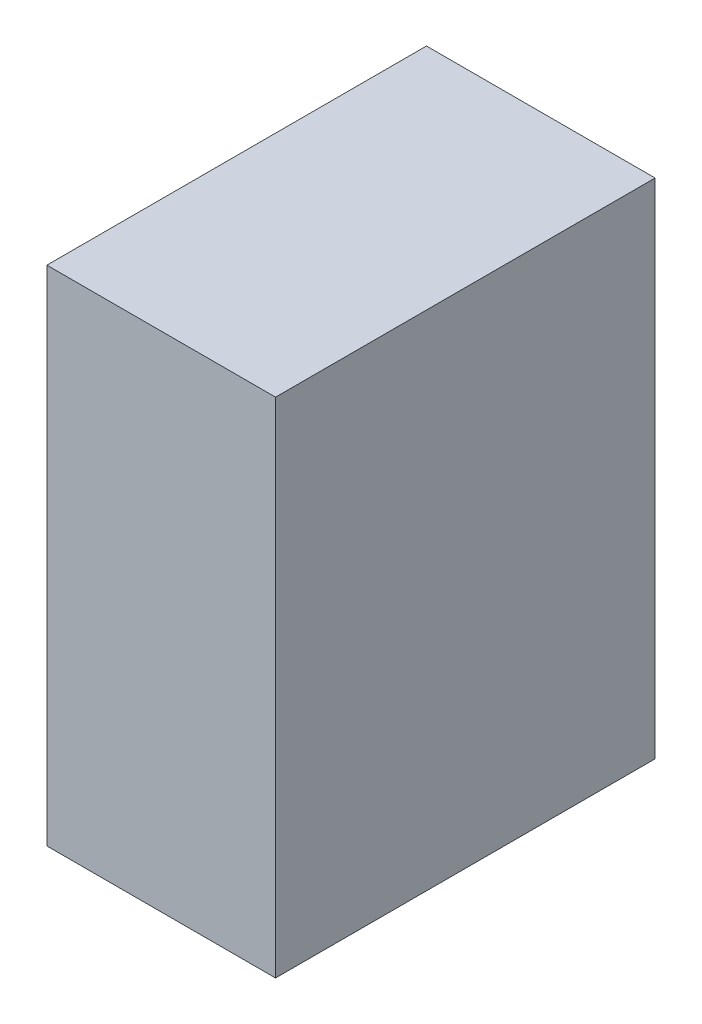
SolidWorks part; units mm, degrees
ref_plane "Front Plane" through (0, 0, 0) normal (0, 0, 1) x (1, 0, 0)
ref_plane "Top Plane" through (0, 0, 0) normal (0, 1, 0) x (1, 0, 0)
ref_plane "Right Plane" through (0, 0, 0) normal (1, 0, 0) x (0, 0, -1)
sketch "Sketch1" plane through (0, 0, 0) normal (0, 0, 1) x (1, 0, 0)
  line L1 (6.35, -12.7) -> (-6.35, -12.7)
  line L2 (6.35, -12.7) -> (6.35, 12.7)
  line L3 (6.35, 12.7) -> (-6.35, 12.7)
  line L4 (-6.35, -12.7) -> (-6.35, 12.7)
  line L5 (6.35, -12.7) -> (-6.35, 12.7) construction
  line L6 (6.35, 12.7) -> (-6.35, -12.7) construction
  point P0 (0, 0)
  dimension "D1" = 12.7
  dimension "D2" = 25.4
extrude "Boss-Extrude1" add sketch "Sketch1" along normal blind 21.082
sketch "Sketch3" plane through (0, 12.7, 0) normal (0, 1, 0) x (1, 0, 0)
  line L0 (0, -21.082) -> (0, 0) construction
  line L1 (6.35, -21.082) -> (-6.35, -21.082) construction
  line L2 (-6.35, -21.082) -> (-6.35, 0) construction
  line L3 (4.064, -18.542) -> (-4.064, -18.542)
  line L4 (4.064, -18.542) -> (4.064, -5.334)
  line L5 (4.064, -5.334) -> (-4.064, -5.334)
  line L6 (-4.064, -18.542) -> (-4.064, -5.334)
  dimension "D1" = 8.128
  dimension "D2" = 13.208
  dimension "D3" = 2.54
  dimension "D4" = 2.286
extrude "Cut-Extrude2" cut sketch "Sketch3" against normal blind 27.94
sketch "Sketch4" plane through (0, 12.7, 0) normal (0, 1, 0) x (1, 0, 0)
  line L0 (6.35, 0) -> (-6.35, 0) construction
  line L1 (-4.064, -5.334) -> (1.016, -5.334)
  line L2 (-4.064, -5.334) -> (-4.064, 0)
  line L3 (-4.064, 0) -> (1.016, 0)
  line L4 (1.016, -5.334) -> (1.016, 0)
  dimension "D1" = 5.08
extrude "Cut-Extrude3" cut sketch "Sketch4" against normal blind 27.94
sketch "Sketch5" plane through (0, 12.7, 0) normal (0, 1, 0) x (1, 0, 0)
  line L1 (6.35, -21.082) -> (-6.35, -21.082)
  line L2 (6.35, -21.082) -> (6.35, 0)
  line L3 (6.35, 0) -> (-6.35, 0)
  line L4 (-6.35, -21.082) -> (-6.35, 0)
extrude "Boss-Extrude2" add sketch "Sketch5" along normal blind 2.54
